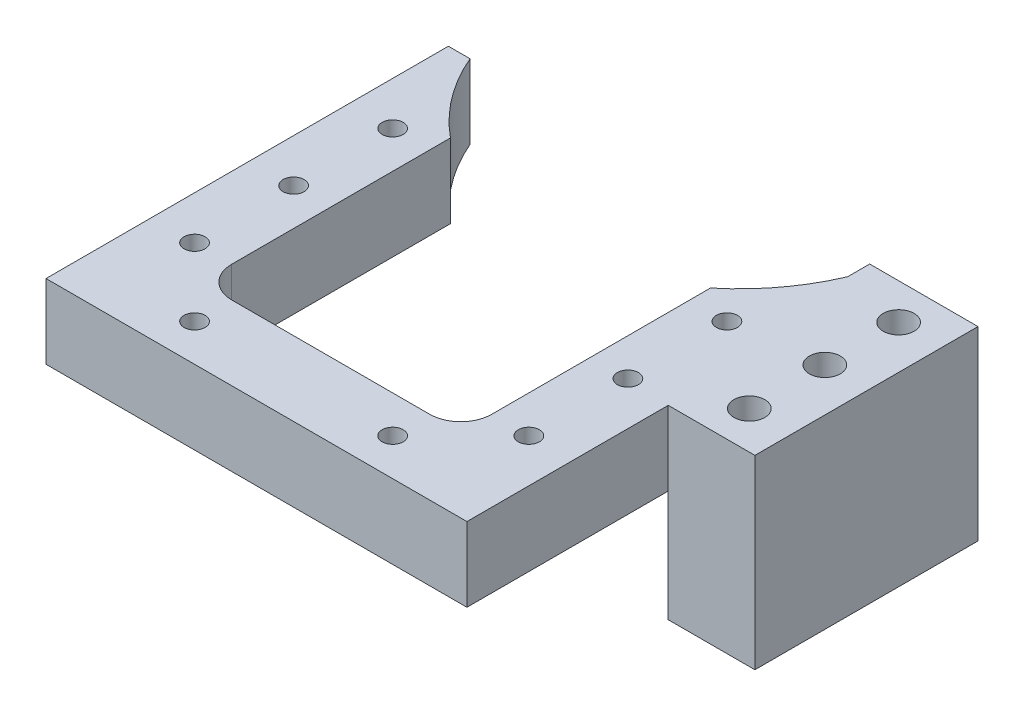
SolidWorks part; units mm, degrees
ref_plane "Front Plane" through (0, 0, 0) normal (0, 0, 1) x (1, 0, 0)
ref_plane "Top Plane" through (0, 0, 0) normal (0, 1, 0) x (1, 0, 0)
ref_plane "Right Plane" through (0, 0, 0) normal (1, 0, 0) x (0, 0, -1)
sketch "Sketch1" plane through (0, 0, 0) normal (0, 1, 0) x (1, 0, 0)
  line L0 (0, 0) -> (0, 11.5) construction
  line L1 (0, 0) -> (0, -36) construction
  line L2 (0, 0) -> (13.5, 0) construction
  line L3 (0, 0) -> (-13.5, 0) construction
  line L4 (-13.5, 0) -> (-13.5, -6.5) construction
  line L5 (-13.5, -6.5) -> (-13.5, -14.5) construction
  line L6 (-13.5, -14.5) -> (-13.5, -22.5) construction
  line L7 (-13.5, -22.5) -> (-13.5, -30.5) construction
  line L8 (-17, -6.5) -> (-17, -33.5)
  line L9 (-17, -33.5) -> (-17, -39)
  line L12 (-13.5, -30.5) -> (-13.5, -36) construction
  line L13 (-13.5, -36) -> (-8, -36) construction
  line L14 (13.5, 0) -> (13.5, -6.5) construction
  line L15 (13.5, -6.5) -> (13.5, -14.5) construction
  line L16 (13.5, -14.5) -> (13.5, -22.5) construction
  line L17 (13.5, -22.5) -> (13.5, -30.5) construction
  line L18 (13.5, -30.5) -> (13.5, -36) construction
  line L19 (13.5, -36) -> (8, -36) construction
  line L20 (-13.5, -6.5) -> (-17, -6.5) construction
  line L21 (-13.5, -6.5) -> (-10, -6.5) construction
  line L22 (13.5, -6.5) -> (10, -6.5) construction
  line L23 (13.5, -6.5) -> (17, -6.5) construction
  line L24 (17, -33.5) -> (17, -39)
  line L25 (17, -6.5) -> (17, -33.5)
  line L26 (13.5, -6.5) -> (17, -6.5) construction
  line L27 (-17, -39) -> (17, -39)
  line L28 (-17, -6.5) -> (-15.25, -6.5)
  line L29 (-10.5, -12.8282) -> (-10.5, -30.5)
  line L30 (-10.5, -30.5) -> (-8, -30.5)
  line L31 (-8, -30.5) -> (-8, -33)
  line L32 (8, -33) -> (-8, -33)
  line L33 (8, -30.5) -> (8, -33)
  line L34 (10.5, -30.5) -> (8, -30.5)
  line L35 (10.5, -12.8282) -> (10.5, -30.5)
  line L36 (17, -6.5) -> (15.25, -6.5)
  circle A0 centre (0, 0) radius 16 construction
  circle A1 centre (0, 0) radius 11 construction
  circle A2 centre (-13.5, -30.5) radius 0.85
  circle A3 centre (-13.5, -22.5) radius 0.85
  circle A4 centre (-13.5, -14.5) radius 0.85
  circle A5 centre (-8, -36) radius 0.85
  circle A6 centre (8, -36) radius 0.85
  circle A7 centre (13.5, -30.5) radius 0.85
  circle A8 centre (13.5, -22.5) radius 0.85
  circle A9 centre (13.5, -14.5) radius 0.85
  arc A10 (-15.25, -6.5) -> (-10.5, -12.8282) centre (0, 0) ccw
  arc A11 (15.25, -6.5) -> (10.5, -12.8282) centre (0, 0) cw
  point P45 (0, -33.5)
  dimension "D1" = 32
  dimension "D2" = 22
  dimension "D3" = 11.5
  dimension "D13" = 1.7
  dimension "D14" = 2.5
  dimension "D4" = 36
  dimension "D5" = 3
  dimension "D6" = 13.5
  dimension "D7" = 6.5
  dimension "D8" = 8
  dimension "D9" = 8
  dimension "D10" = 8
  dimension "D11" = 5.5
  dimension "D12" = 5.5
  dimension "D15" = 3.5
  dimension "D16" = 3.5
  dimension "D17" = 3.5
  dimension "D18" = 3
  dimension "D19" = 13.5
  dimension "D20" = 3
extrude "Boss-Extrude1" add sketch "Sketch1" along normal blind 6
sketch "Sketch2" plane through (0, 0, 0) normal (0, -1, 0) x (1, 0, 0)
  line L0 (10.5, 12.8282) -> (10.5, 17.3382) construction
  line L1 (10.5, 12.8282) -> (10.5, 30.5) construction
  line L2 (10.5, 17.3382) -> (10.5, 19.3382) construction
  circle A0 centre (10.5, 19.3382) radius 2
  dimension "D3" = 4
  dimension "D1" = 4.51
  dimension "D2" = 2
sketch "Sketch3" plane through (0, 0, 0) normal (0, -1, 0) x (1, 0, 0)
  line L0 (17, 22.74) -> (24, 22.74)
  line L3 (24, 22.74) -> (24, 4.72)
  line L4 (24, 4.72) -> (17, 4.72)
  line L5 (17, 4.72) -> (17, 7.9018)
  line L6 (17, 22.74) -> (17, 7.9018)
  dimension "D1" = 16.26
  dimension "D2" = 7
  dimension "D3" = 18.02
extrude "Boss-Extrude2" add sketch "Sketch3" against normal blind 6 and the other way blind 9
sketch "Sketch4" plane through (0, -9, 0) normal (0, -1, 0) x (1, 0, 0)
  line L0 (17, 22.74) -> (17, 10.54) construction
  line L1 (17, 10.54) -> (24, 10.54) construction
  line L2 (24, 4.72) -> (24, 22.74) construction
  line L4 (17, 10.54) -> (17, 4.72) construction
  line L5 (24, 4.72) -> (17, 10.54) construction
  line L6 (24, 10.54) -> (17, 4.72) construction
  line L9 (24, 16.64) -> (17, 16.64) construction
  line L10 (24, 10.54) -> (17, 16.64) construction
  line L11 (17, 10.54) -> (24, 16.64) construction
  line L12 (24, 16.64) -> (17, 22.74) construction
  line L13 (17, 16.64) -> (24, 22.74) construction
  circle A0 centre (20.5, 7.63) radius 1.25
  circle A1 centre (20.5, 13.59) radius 1.25
  circle A2 centre (20.5, 19.69) radius 1.25
  dimension "D1" = 12.2
  dimension "D2" = 2.5
extrude "Cut-Extrude2" cut sketch "Sketch4" against normal through all
sketch "Sketch5" plane through (0, 0, 0) normal (0, -1, 0) x (1, 0, 0)
  line L1 (8, 30.5) -> (8, 33) construction
  line L2 (8, 33) -> (-8, 33)
  line L3 (-8, 33) -> (-8, 30.5) construction
  line L4 (-8, 30.5) -> (-10.5, 30.5) construction
  line L5 (10.5, 30.5) -> (-10.5, 30.5)
  arc A0 (10.5, 30.5) -> (8, 33) centre (8, 30.5) ccw
  arc A1 (-8, 33) -> (-10.5, 30.5) centre (-8, 30.5) ccw
extrude "Cut-Extrude3" cut sketch "Sketch5" against normal blind 10
sketch "Sketch7" plane through (0, 6, 0) normal (0, 1, 0) x (1, 0, 0)
  line L0 (17, -4.72) -> (15.25, -4.72)
  line L1 (15.25, -4.72) -> (15.25, -6.5)
  line L2 (15.25, -6.5) -> (17, -6.5)
  line L3 (17, -6.5) -> (17, -4.72)
extrude "Boss-Extrude4" add sketch "Sketch7" against normal up to surface (6 mm away) up to face at (1.3077, 0, 21.6159)
